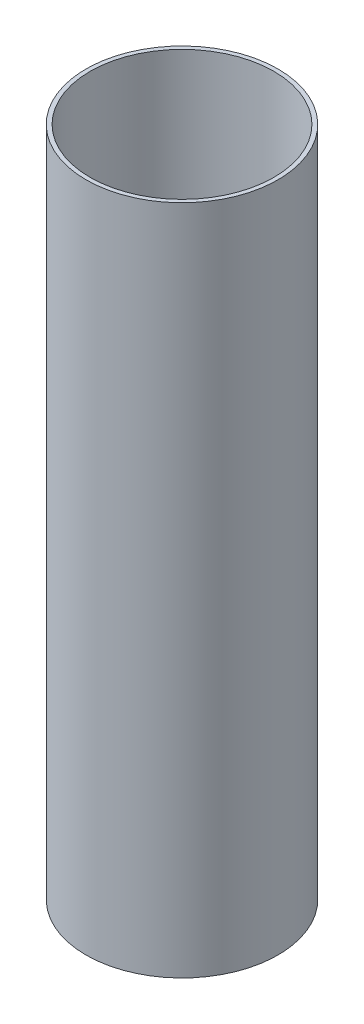
SolidWorks part; units mm, degrees
material "PET"
ref_plane "Płaszczyzna przednia" through (0, 0, 0) normal (0, 0, 1) x (1, 0, 0)
ref_plane "Płaszczyzna górna" through (0, 0, 0) normal (0, 1, 0) x (1, 0, 0)
ref_plane "Płaszczyzna prawa" through (0, 0, 0) normal (1, 0, 0) x (0, 0, -1)
sketch "Szkic1" plane through (0, 0, 0) normal (0, 1, 0) x (1, 0, 0)
  circle A0 centre (0, 0) radius 64.775
  circle A1 centre (0, 0) radius 62
  dimension "D1" = 129.55
  dimension "D2" = 124
extrude "Dodanie-wyciągnięcie1" add sketch "Szkic1" along normal blind 453
ref_plane "Płaszczyzna1" through (0, 453, 0) normal (0, 1, 0) x (1, 0, 0)
